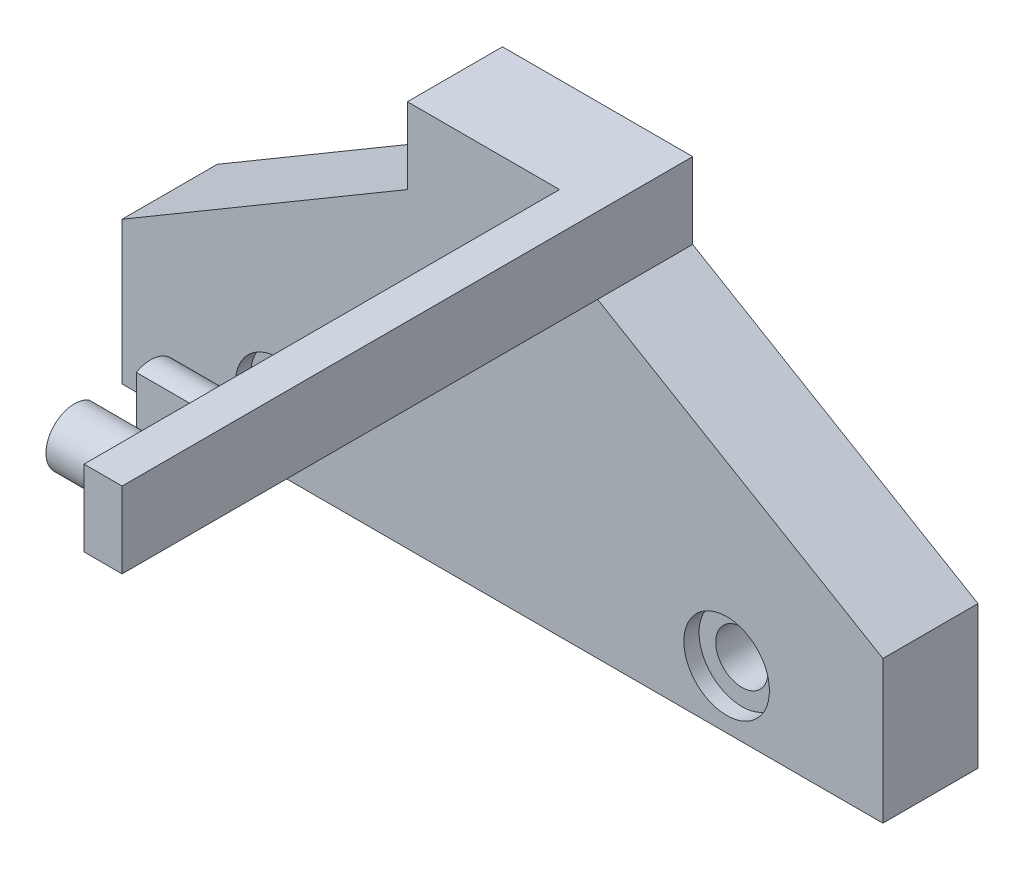
SolidWorks part; units mm, degrees
ref_plane "Front Plane" through (0, 0, 0) normal (0, 0, 1) x (1, 0, 0)
ref_plane "Top Plane" through (0, 0, 0) normal (0, 1, 0) x (1, 0, 0)
ref_plane "Right Plane" through (0, 0, 0) normal (1, 0, 0) x (0, 0, -1)
sketch "Sketch2" plane through (0, 0, 0) normal (0, 0, 1) x (1, 0, 0)
  line L0 (-24.3822, 22.6401) -> (-54.3822, 4.9401)
  line L2 (-54.3822, 4.9401) -> (-54.3822, -10.0599)
  line L3 (-54.3822, -10.0599) -> (25.6178, -10.0599)
  line L4 (25.6178, 4.9401) -> (25.6178, -10.0599)
  line L5 (-24.3822, 30.6401) -> (-4.3822, 30.6401)
  line L6 (-24.3822, 30.6401) -> (-24.3822, 22.6401)
  line L8 (-4.3822, 30.6401) -> (-4.3822, 22.6401)
  line L9 (-4.3822, 22.6401) -> (25.6178, 4.9401)
  point P8 (-14.3822, 30.6401)
  point P9 (-14.3822, -10.0599)
  dimension "D1" = 8
  dimension "D2" = 20
  dimension "D3" = 80
  dimension "D4" = 25.7
  dimension "D5" = 15
extrude "Boss-Extrude1" add sketch "Sketch2" along normal blind 10
ref_plane "Plane1" through (-14.3822, 0, 0) normal (-1, 0, 0) x (0, 0, 1)
sketch "Sketch4" plane through (0, 0, 10) normal (0, 0, 1) x (1, 0, 0)
  line L0 (-54.3822, 4.9401) -> (-54.3822, -10.0599) construction
  circle A0 centre (-37.9522, -3.9599) radius 2.75
  dimension "D1" = 5.5
  dimension "D2" = 8.9
  dimension "D3" = 16.43
extrude "Cut-Extrude1" cut sketch "Sketch4" against normal through all
mirror "Mirror2" about plane through (-14.3822, 0, 0) normal (-1, 0, 0) of "Cut-Extrude1"
sketch "Sketch6" plane through (0, 0, 10) normal (0, 0, 1) x (1, 0, 0)
  circle A0 centre (-37.9522, -3.9599) radius 4.5
  circle A1 centre (9.1878, -3.9599) radius 4.5
  dimension "D1" = 9
extrude "Cut-Extrude3" cut sketch "Sketch6" against normal blind 1.6
sketch "Sketch7" plane through (0, 0, 10) normal (0, 0, 1) x (1, 0, 0)
  line L0 (-4.3822, 30.6401) -> (-24.3822, 30.6401) construction
  line L1 (-4.3822, 22.6401) -> (-8.3822, 22.6401)
  line L2 (-4.3822, 22.6401) -> (-4.3822, 30.6401)
  line L3 (-4.3822, 30.6401) -> (-8.3822, 30.6401)
  line L4 (-8.3822, 22.6401) -> (-8.3822, 30.6401)
  dimension "D1" = 4
extrude "Boss-Extrude2" add sketch "Sketch7" along normal blind 50
sketch "Sketch8" plane through (-8.3822, 0, 0) normal (-1, 0, 0) x (0, 0, 1)
  line L1 (60, 30.6401) -> (10, 30.6401) construction
  line L2 (60, 30.6401) -> (60, 22.6401) construction
  circle A0 centre (54, 26.6401) radius 3
  circle A1 centre (46, 26.6401) radius 3
  point P8 (0, 0)
  dimension "D2" = 6
  dimension "D1" = 6
  dimension "D3" = 4
  dimension "D4" = 8
extrude "Boss-Extrude3" add sketch "Sketch8" along normal blind 7
sketch "Sketch9" plane through (-8.3822, 0, 0) normal (-1, 0, 0) x (0, 0, 1)
  line L0 (46, 26.6401) -> (54, 26.6401) construction
  line L1 (47.5, 22.6401) -> (52.5, 22.6401)
  line L2 (47.5, 22.6401) -> (47.5, 30.6401)
  line L3 (47.5, 30.6401) -> (52.5, 30.6401)
  line L4 (52.5, 22.6401) -> (52.5, 30.6401)
  line L5 (47.5, 22.6401) -> (52.5, 30.6401) construction
  line L6 (47.5, 30.6401) -> (52.5, 22.6401) construction
  line L7 (60, 30.6401) -> (10, 30.6401) construction
  point P0 (50, 26.6401)
  point P9 (50, 26.6401)
  dimension "D1" = 5
extrude "Cut-Extrude4" cut sketch "Sketch9" along normal through all
